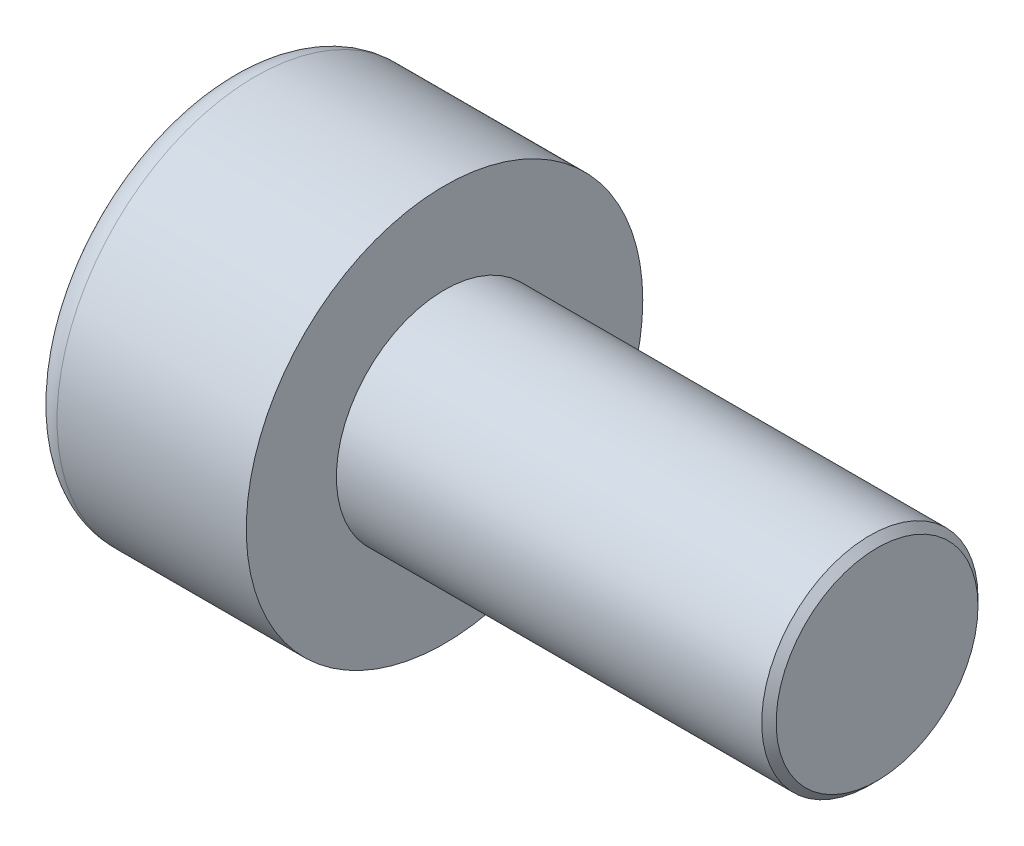
SolidWorks part; units mm, degrees
ref_plane "Front" through (0, 0, 0) normal (0, 0, 1) x (1, 0, 0)
ref_plane "Top" through (0, 0, 0) normal (0, 1, 0) x (1, 0, 0)
ref_plane "Right" through (0, 0, 0) normal (1, 0, 0) x (0, 0, -1)
other "Configuration Table"
sketch "Sketch1" plane through (0, 0, 0) normal (1, 0, 0) x (0, 0, -1)
  circle A0 centre (0, 0) radius 2.75
  dimension "dk" = 5.5
extrude "BaseHead" add sketch "Sketch1" along normal blind 3
sketch "Sketch2" plane through (3, 0, 0) normal (1, 0, 0) x (0, 0, -1)
  circle A0 centre (0, 0) radius 1.5
extrude "BaseBody" add sketch "Sketch2" along normal blind 6
cosmetic thread "ThreadCosmetic1" [suppressed] parameters "b"=6, "D2"=2.459
sketch "Sketch3" plane through (0, 0, 0) normal (1, 0, 0) x (0, 0, -1)
  line L1 (1.4434, 0) -> (0.7217, 1.25)
  line L2 (0.7217, 1.25) -> (-0.7217, 1.25)
  line L3 (-0.7217, 1.25) -> (-1.4434, 0)
  line L4 (-1.4434, 0) -> (-0.7217, -1.25)
  line L5 (-0.7217, -1.25) -> (0.7217, -1.25)
  line L6 (0.7217, -1.25) -> (1.4434, 0)
  circle A0 centre (0, 0) radius 1.25 construction
  dimension "s" = 2.5
  dimension "e" = 2.8868
extrude "HexagonSocket" cut sketch "Sketch3" along normal blind 1.3
sketch "Sketch4" plane through (-4.1961, 0.75, 0) normal (0, 0, 1) x (-1, 0, 0)
  line L0 (-5.4961, 2) -> (-6.2178, 0.75)
  line L2 (-6.2178, 0.75) -> (-5.4961, 0.75)
  line L3 (-5.4961, 0.75) -> (-5.4961, 2)
  line L4 (-5.0351, 0.75) -> (0.839, 0.75) construction
  line L5 (-13.1961, 0.75) -> (-7.1961, 0.75) construction
  line L6 (-7.1961, 0.75) -> (-4.1961, 0.75) construction
  dimension "m" = 60
revolve "Cut-Revolve1" cut sketch "Sketch4" angle 360 about L4
fillet "HeadFillet" [suppressed] radius 0.1
fillet "TopFillet" radius 0.375 1 edges at (0, 0, -2.75)
chamfer "Chamfer1" distance 0.1 angle 45 1 edges at (9, 0, -1.5)
sketch "Sketch5" plane through (0, 0, 0) normal (0, 0, 1) x (1, 0, 0)
  line L0 (8.9, 1.2657) -> (9.0353, 1.5)
  line L1 (9.0353, 1.5) -> (9.0353, 1.7705)
  line L2 (9.0353, 1.7705) -> (8.7648, 1.7705)
  line L3 (8.7648, 1.7705) -> (8.7648, 1.5)
  line L4 (8.7648, 1.5) -> (8.9, 1.2657)
  line L5 (0, 0) -> (7.8886, 0) construction
  line L6 (8.9, -1.5) -> (8.9, 1.5) construction
revolve "Cut-Revolve10" [suppressed] cut sketch "Sketch5" angle 360 about L5
pattern_linear "LPattern10" [suppressed] count 18 spacing 0.3246 along (1, 0, 0)
equation "\"r1@TopFillet\" = \"d@Sketch2\" / 8"
equation "\"D1@Chamfer1\" = \"r@HeadFillet\""
equation "\"D1@Sketch5\" = \"d@Sketch2\""
equation "\"D2@Sketch5\" =  ( \"d@Sketch2\" - \"D2@ThreadCosmetic1\" )  / 2"
equation "\"D3@LPattern10\" = \"D2@Sketch5\" * 1.2"
equation "\"D1@LPattern10\" = \"b@ThreadCosmetic1\" / \"D3@LPattern10\""
